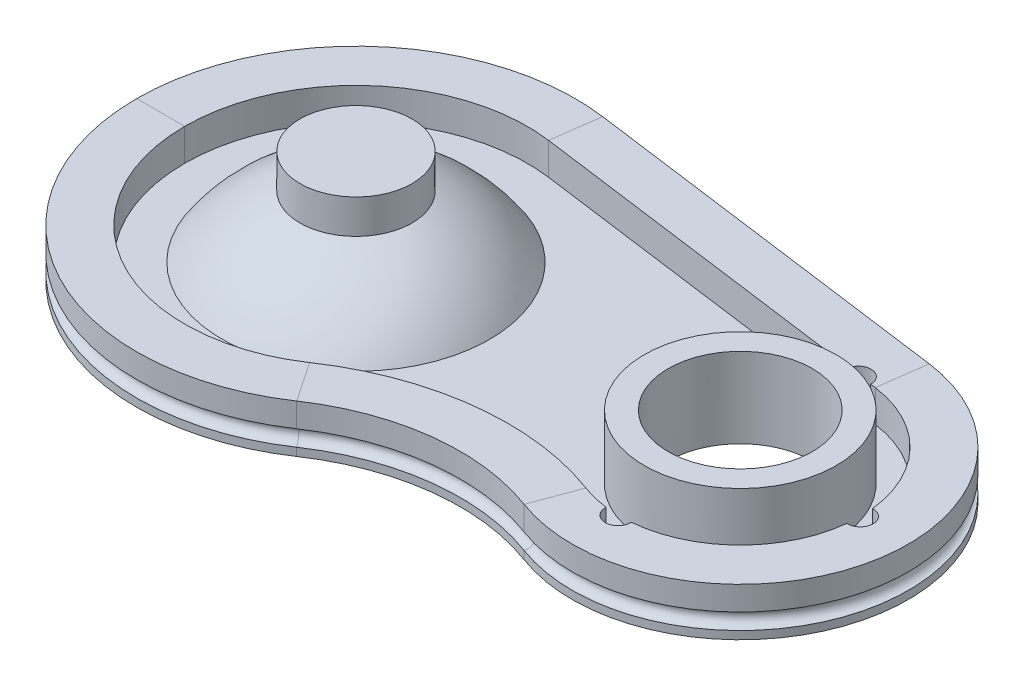
SolidWorks part; units mm, degrees
ref_plane "Front Plane" through (0, 0, 0) normal (0, 0, 1) x (1, 0, 0)
ref_plane "Top Plane" through (0, 0, 0) normal (0, 1, 0) x (1, 0, 0)
ref_plane "Right Plane" through (0, 0, 0) normal (1, 0, 0) x (0, 0, -1)
sketch "Sketch2" plane through (0, 0, 0) normal (0, 1, 0) x (1, 0, 0)
  line L0 (0, 0) -> (240, 0) construction
  line L1 (254, 104.0625) -> (18.2667, 135.7768)
  arc A0 (18.2667, 135.7768) -> (76.5617, -113.6103) centre (0, 0) ccw
  arc A1 (203.4857, -98.4465) -> (254, 104.0625) centre (240, 0) ccw
  arc A2 (76.5617, -113.6103) -> (203.4857, -98.4465) centre (154.8, -229.7084) cw
  dimension "D1" = 274
  dimension "D2" = 210
  dimension "D4" = 140
  dimension "D3" = 240
sketch "Sketch3" plane through (0, 0, 0) normal (0, 0, 1) x (1, 0, 0)
  line L1 (-107, 0) -> (-137, 0)
  line L2 (-107, 0) -> (-107, 30)
  line L3 (-107, 30) -> (-137, 30)
  line L4 (-137, 0) -> (-137, 5)
  line L8 (-137, 15) -> (-137, 30)
  arc A0 (-137, 5) -> (-137, 15) centre (-137, 10) ccw
  dimension "D3" = 5
  dimension "D1" = 30
  dimension "D2" = 30
  dimension "D4" = 10
sweep "Sweep1" add profiles "Sketch3" path "Sketch2"
sketch "Sketch6" plane through (0, 0, 0) normal (1, 0, 0) x (0, 0, -1)
  line L0 (0, 45) -> (0, 70)
  line L1 (0, 0) -> (60, 0) construction
  line L2 (60, 10) -> (60, 22.082)
  line L4 (0, 70) -> (35, 70)
  line L5 (35, 70) -> (35, 48.675)
  line L7 (60, 10) -> (83.5165, 10)
  line L8 (0, 45) -> (0, 0) construction
  arc A0 (83.5165, 10) -> (35, 48.675) centre (0, -45) ccw
  arc A1 (60, 22.082) -> (-0.0116, 45) centre (0, -45) ccw
  dimension "D1" = 90
  dimension "D2" = 100
  dimension "D3" = 70
  dimension "D4" = 60
  dimension "D5" = 35
  dimension "D6" = 10
  dimension "D7" = 45
sketch "Sketch7" plane through (0, 0, 0) normal (0, 1, 0) x (1, 0, 0)
  line L0 (250, 74.3303) -> (14.2667, 106.0446) construction
  line L1 (250, 74.3303) -> (14.2667, 106.0446)
  arc A0 (-107, 0) -> (59.7964, -88.7321) centre (0, 0) ccw construction
  arc A1 (14.2667, 106.0446) -> (-107, 0) centre (0, 0) ccw construction
  arc A2 (213.9184, -70.3189) -> (250, 74.3303) centre (240, 0) ccw construction
  arc A3 (213.9184, -70.3189) -> (59.7964, -88.7321) centre (154.8, -229.7084) ccw construction
  arc A4 (-107, 0) -> (59.7964, -88.7321) centre (0, 0) ccw
  arc A5 (14.2667, 106.0446) -> (-107, 0) centre (0, 0) ccw
  arc A6 (213.9184, -70.3189) -> (250, 74.3303) centre (240, 0) ccw
  arc A7 (213.9184, -70.3189) -> (59.7964, -88.7321) centre (154.8, -229.7084) ccw
extrude "Boss-Extrude1" add sketch "Sketch7" along normal blind 10
ref_plane "Plane1" through (240, 0, 0) normal (1, 0, 0) x (0, 0, -1)
sketch "Sketch8" plane through (240, 0, 0) normal (1, 0, 0) x (0, 0, -1)
  line L0 (0, 0) -> (35, 0) construction
  line L1 (137, 0) -> (-137, 0) construction
  line L2 (35, 0) -> (35, 10)
  line L3 (35, 10) -> (45, 10)
  line L4 (45, 10) -> (45, 50)
  line L5 (45, 50) -> (60, 50)
  line L6 (60, 50) -> (60, 0)
  line L7 (60, 0) -> (35, 0)
  line L8 (0, 0) -> (0, 35.2733) construction
  dimension "D1" = 60
  dimension "D2" = 35
  dimension "D3" = 45
  dimension "D4" = 50
  dimension "D5" = 40
revolve "Revolve1" add sketch "Sketch8" angle 360 about L8
sketch "Sketch9" plane through (0, 10, 0) normal (0, 1, 0) x (1, 0, 0)
  circle A1 centre (240, 0) radius 45
  circle A3 centre (240, 0) radius 45
  dimension "D1" = 0
extrude "Cut-Extrude1" cut sketch "Sketch9" against normal through all
sketch "Sketch10" plane through (0, 30, 0) normal (0, 1, 0) x (1, 0, 0)
  arc A0 (213.9184, -70.3189) -> (250, 74.3303) centre (240, 0) ccw construction
  arc A1 (213.9184, -70.3189) -> (250, 74.3303) centre (240, 0) ccw construction
  circle A3 centre (315, 0) radius 8
  dimension "D2" = 16
extrude "Cut-Extrude2" cut sketch "Sketch10" against normal through all
pattern_circular "CirPattern1" count 2 every 91 about axis through (240, 10, 0) along (0, 1, 0) of "Cut-Extrude2"
ref_plane "Plane2" through (0, 0, 0) normal (1, 0, 0) x (0, 0, -1)
sketch "Sketch12" plane through (0, 0, 0) normal (1, 0, 0) x (0, 0, -1)
  line L0 (60, 10) -> (60, 22.082) construction
  line L1 (35, 70) -> (35, 48.675) construction
  line L3 (0, 70) -> (35, 70) construction
  line L4 (60, 10) -> (60, 22.082)
  line L5 (35, 70) -> (35, 48.675)
  line L6 (-0.0116, 45) -> (0, 70)
  line L7 (0, 70) -> (35, 70)
  line L8 (60, 10) -> (83.5165, 10)
  line L9 (-66.9886, 10) -> (-74.7014, 10) construction
  line L10 (0, 10) -> (0, 45) construction
  line L11 (0, 45) -> (0, 0) construction
  arc A0 (60, 22.082) -> (-0.0116, 45) centre (0, -45) ccw construction
  arc A1 (83.5165, 10) -> (35, 48.675) centre (0, -45) ccw construction
  arc A2 (60, 22.082) -> (-0.0116, 45) centre (0, -45) ccw
  arc A3 (83.5165, 10) -> (35, 48.675) centre (0, -45) ccw
  dimension "D1" = 35
  dimension "D2" = 60
sketch "Sketch13" plane through (0, 10, 0) normal (0, 1, 0) x (1, 0, 0)
  circle A0 centre (0, 0) radius 60
  dimension "D1" = 120
extrude "Cut-Extrude3" cut sketch "Sketch13" against normal through all
revolve "Revolve4" add sketch "Sketch12" angle 360 about L6
